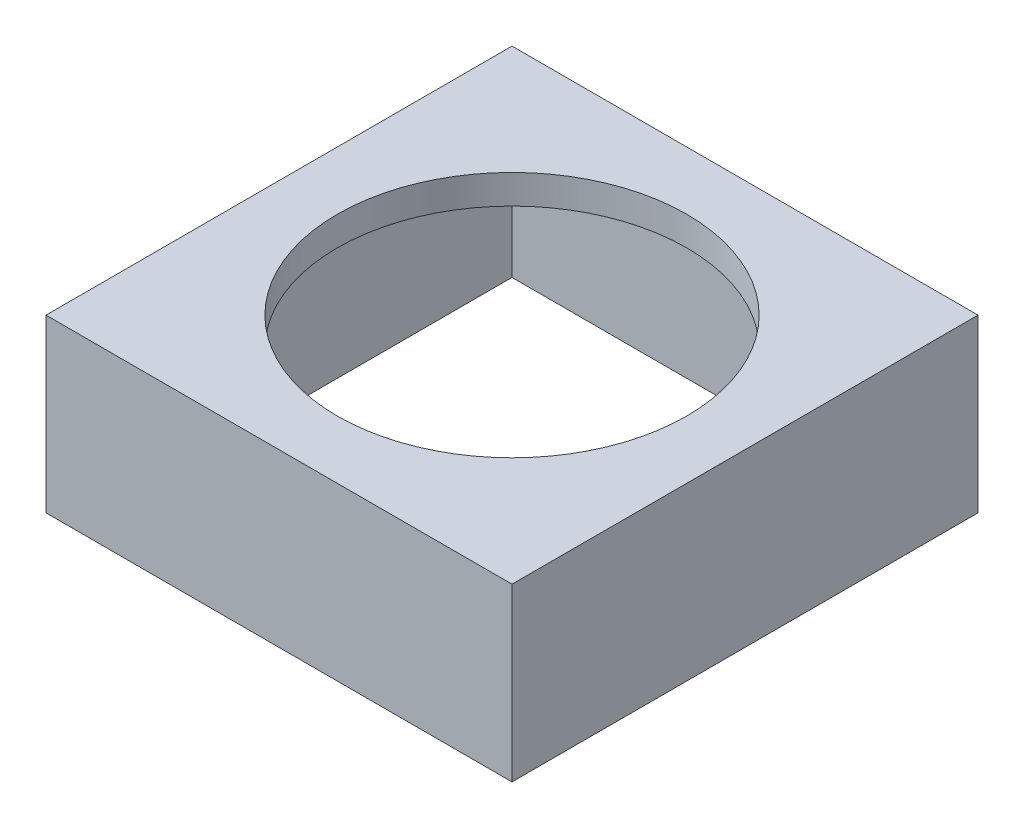
SolidWorks part; units mm, degrees
ref_plane "Front Plane" through (0, 0, 0) normal (0, 0, 1) x (1, 0, 0)
ref_plane "Top Plane" through (0, 0, 0) normal (0, 1, 0) x (1, 0, 0)
ref_plane "Right Plane" through (0, 0, 0) normal (1, 0, 0) x (0, 0, -1)
sketch "Sketch1" plane through (0, 0, 0) normal (0, 1, 0) x (1, 0, 0)
  line L5 (-3.5, 3.5) -> (3.5, 3.5)
  line L6 (-3.5, 3.5) -> (-3.5, -3.5)
  line L7 (-3.5, -3.5) -> (3.5, -3.5)
  line L8 (3.5, 3.5) -> (3.5, -3.5)
  line L9 (-4, 4) -> (4, 4)
  line L10 (-4, 4) -> (-4, -4)
  line L11 (-4, -4) -> (4, -4)
  line L12 (4, 4) -> (4, -4)
  dimension "D1" = 7
  dimension "D2" = 7
  dimension "D3" = 3.5
  dimension "D4" = 3.5
  dimension "D5" = 0.5
  dimension "D6" = 0.5
  dimension "D7" = 0.5
  dimension "D8" = 0.5
extrude "Boss-Extrude1" add sketch "Sketch1" along normal blind 2.94
sketch "Sketch2" plane through (0, 2.94, 0) normal (0, 1, 0) x (1, 0, 0)
  line L1 (-4, 4) -> (4, 4)
  line L2 (-4, 4) -> (-4, -4)
  line L3 (-4, -4) -> (4, -4)
  line L4 (4, 4) -> (4, -4)
  circle A0 centre (0, 0) radius 3
  dimension "D1" = 6
extrude "Boss-Extrude2" add sketch "Sketch2" against normal blind 0.5
